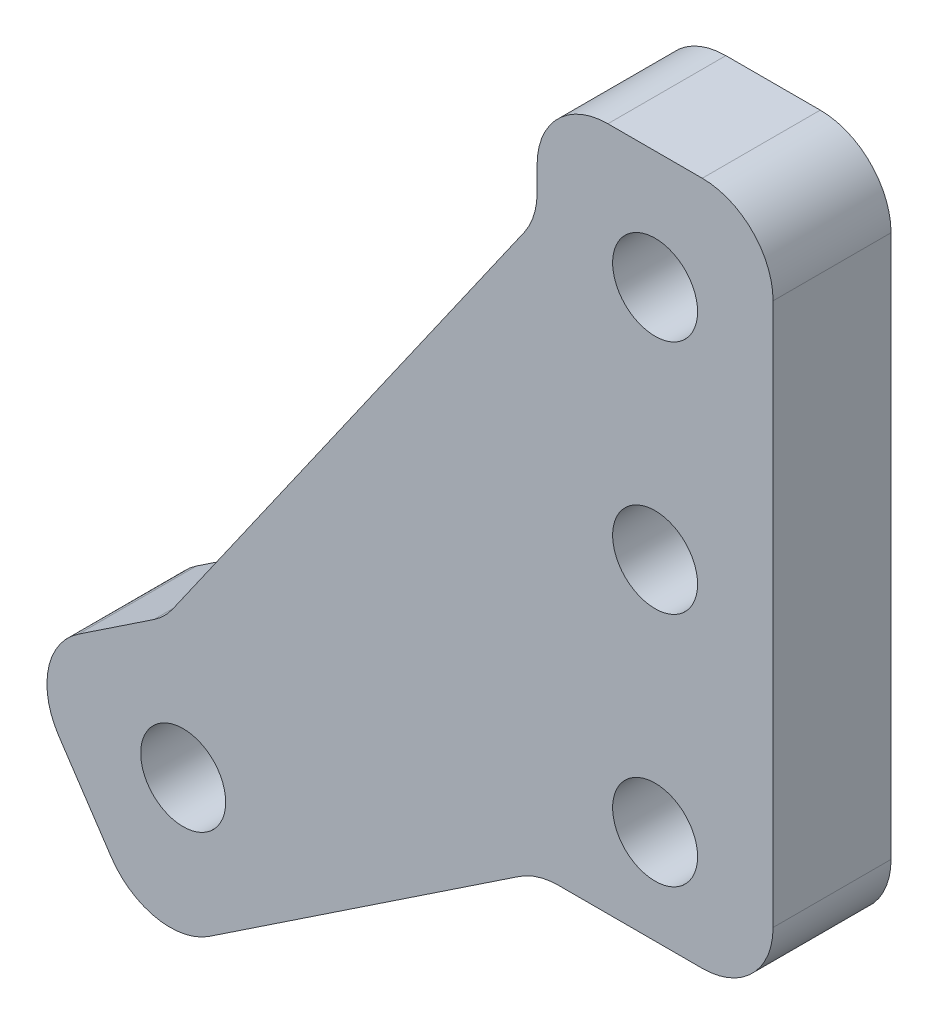
SolidWorks part; units mm, degrees
ref_plane "Front Plane" through (0, 0, 0) normal (0, 0, 1) x (1, 0, 0)
ref_plane "Top Plane" through (0, 0, 0) normal (0, 1, 0) x (1, 0, 0)
ref_plane "Right Plane" through (0, 0, 0) normal (1, 0, 0) x (0, 0, -1)
sketch "Sketch1" plane through (0, 0, 0) normal (0, 0, 1) x (1, 0, 0)
  line L0 (-6.35, 31.75) -> (-6.35, 10.1888)
  line L1 (-6.35, 10.1888) -> (-34.2068, -8.4034)
  line L2 (-34.2068, -8.4034) -> (-27.1566, -18.9668)
  line L4 (6.35, -5.08) -> (6.35, 31.75)
  line L5 (6.35, 31.75) -> (-6.35, 31.75)
  line L6 (6.35, -5.08) -> (-6.35, -5.08)
  line L7 (-6.35, -5.08) -> (-27.1566, -18.9668)
  circle A0 centre (0, 0) radius 2.286
  circle A1 centre (0, 25.4) radius 2.286
  circle A2 centre (-25.4, -10.16) radius 2.286
  circle A3 centre (0, 12.7) radius 2.286
  dimension "D2" = 4.572
  dimension "D1" = 25.4
  dimension "D3" = 10.16
  dimension "D4" = 6.35
  dimension "D5" = 6.35
  dimension "D6" = 6.35
  dimension "D7" = 12.7
  dimension "D8" = 6.35
  dimension "D9" = 12.7
  dimension "D10" = 5.08
  dimension "D11" = 25.4
  dimension "D12" = 12.7
extrude "Boss-Extrude1" add sketch "Sketch1" along normal blind 6.35
chamfer "Chamfer1" distance 15.24 angle 35 1 edges at (-6.35, 10.1888, 3.175)
fillet "Fillet1" radius 3.81 8 edges at (6.35, 31.75, 3.175) (-6.35, 31.75, 3.175) (-34.2068, -8.4034, 3.175) (6.35, -5.08, 3.175) (-6.35, -5.08, 3.175) (-27.1566, -18.9668, 3.175) (-6.35, 25.4288, 3.175) (-26.3835, -3.182, 3.175)
